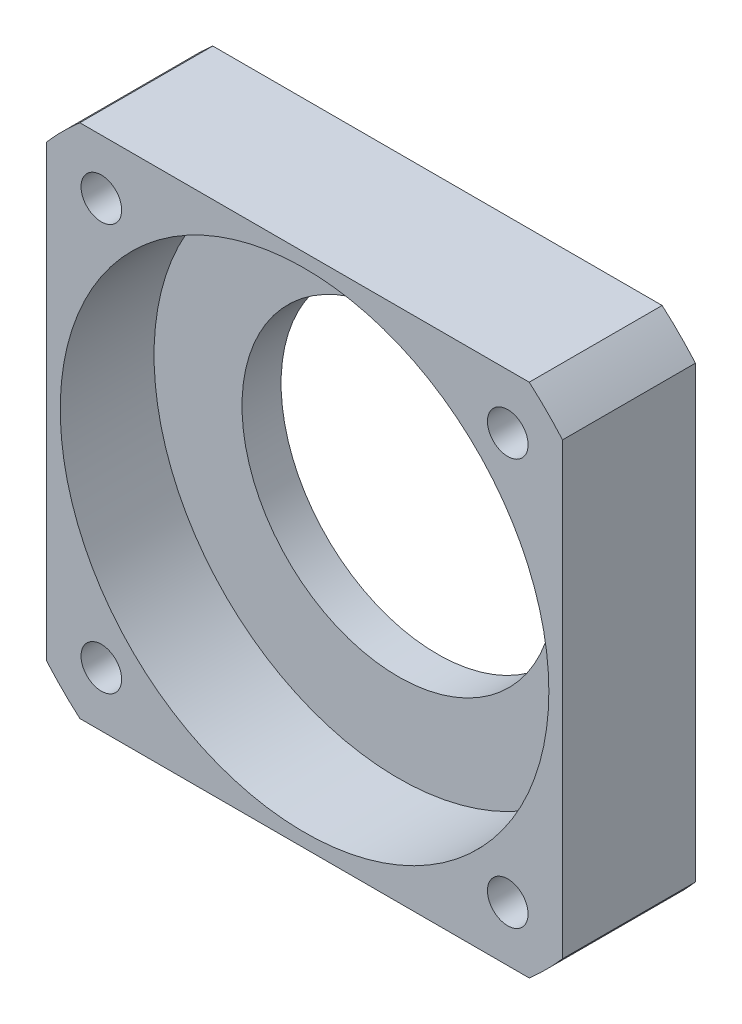
SolidWorks part; units mm, degrees
material "2024-T3"
ref_plane "Front Plane" through (0, 0, 0) normal (0, 0, 1) x (1, 0, 0)
ref_plane "Top Plane" through (0, 0, 0) normal (0, 1, 0) x (1, 0, 0)
ref_plane "Right Plane" through (0, 0, 0) normal (1, 0, 0) x (0, 0, -1)
sketch "Sketch1" plane through (0, 0, 0) normal (0, 0, 1) x (1, 0, 0)
  line L0 (0, 0) -> (41.91, 41.91) construction
  line L1 (0, 0) -> (41.91, 0)
  line L2 (0, 0) -> (0, 41.91)
  line L3 (0, 41.91) -> (41.91, 41.91)
  line L4 (41.91, 0) -> (41.91, 41.91)
  line L5 (4.4493, 37.4607) -> (20.955, 20.955) construction
  circle A0 centre (37.4607, 37.4607) radius 1.6497
  circle A1 centre (37.4607, 4.4493) radius 1.6497
  circle A2 centre (4.4493, 4.4493) radius 1.6497
  circle A3 centre (4.4493, 37.4607) radius 1.6497
  circle A4 centre (20.955, 20.955) radius 12.7
  point P7 (20.955, 20.955)
  point P17 (20.955, 20.955)
  dimension "D3" = 3.2995
  dimension "D7" = 25.4
  dimension "D1" = 41.91
  dimension "D2" = 41.91
  dimension "D4" = 23.3426
  dimension "D6" = 23.3426
  dimension "D5" = 4
extrude "Boss-Extrude1" add sketch "Sketch1" along normal blind 10.795
sketch "Sketch2" plane through (0, 0, 10.795) normal (0, 0, 1) x (1, 0, 0)
  circle A0 centre (20.955, 20.955) radius 27.7876
  circle A1 centre (20.955, 20.955) radius 62.5657
  dimension "D1" = 55.5752
extrude "Cut-Extrude1" cut sketch "Sketch2" against normal through all
sketch "Sketch3" plane through (0, 0, 10.795) normal (0, 0, 1) x (1, 0, 0)
  circle A0 centre (20.955, 20.955) radius 19.8438
  dimension "D1" = 39.6875
extrude "Cut-Extrude2" cut sketch "Sketch3" against normal blind 7.62
